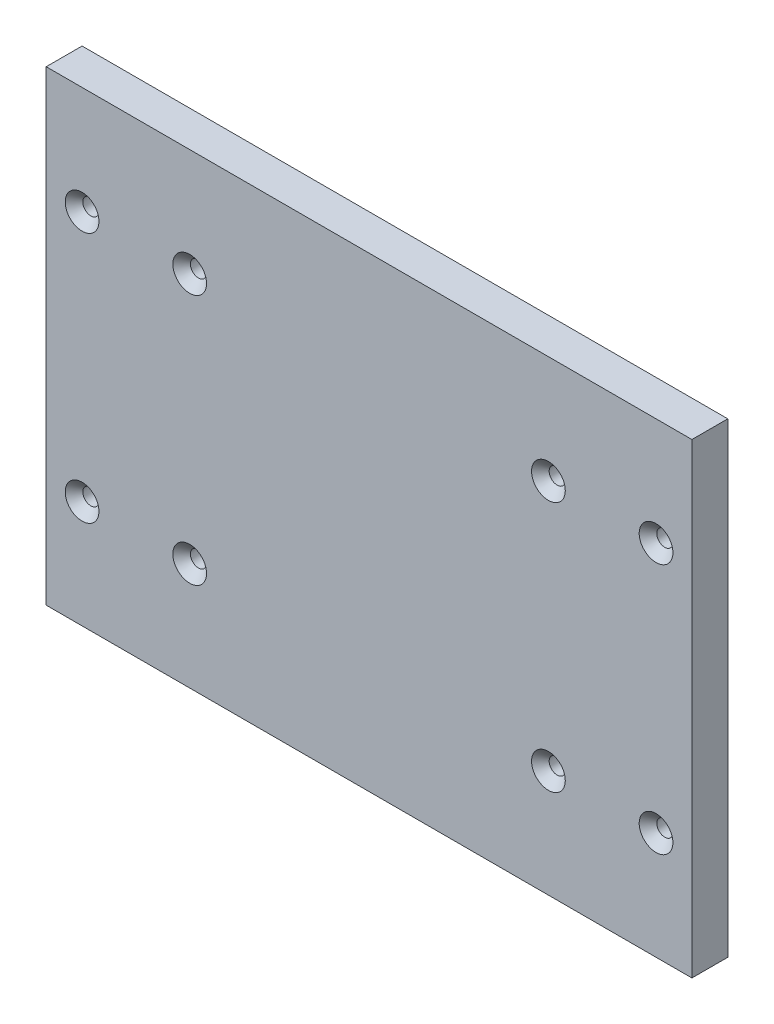
SolidWorks part; units mm, degrees
ref_plane "Front Plane" through (0, 0, 0) normal (0, 0, 1) x (1, 0, 0)
ref_plane "Top Plane" through (0, 0, 0) normal (0, 1, 0) x (1, 0, 0)
ref_plane "Right Plane" through (0, 0, 0) normal (1, 0, 0) x (0, 0, -1)
sketch "Sketch1" plane through (0, 0, 0) normal (0, 0, 1) x (1, 0, 0)
  line L1 (0, 0) -> (180, 0)
  line L2 (0, 0) -> (0, 130)
  line L3 (0, 130) -> (180, 130)
  line L4 (180, 0) -> (180, 130)
extrude "Boss-Extrude1" add sketch "Sketch1" along normal blind 10
sketch "Sketch2" plane through (0, 0, 10) normal (0, 0, 1) x (1, 0, 0)
  line L0 (0, 130) -> (0, 0) construction
  line L1 (10, 100) -> (170, 100)
  line L2 (10, 100) -> (10, 30)
  line L3 (10, 30) -> (170, 30)
  line L4 (170, 100) -> (170, 30)
  line L5 (180, 0) -> (180, 130) construction
  line L6 (180, 130) -> (0, 130) construction
  line L7 (0, 0) -> (180, 0) construction
  line L9 (10, 100) -> (40, 100)
  line L10 (10, 100) -> (10, 30)
  line L11 (10, 30) -> (40, 30)
  line L12 (40, 100) -> (40, 30)
  line L13 (170, 100) -> (140, 100)
  line L14 (170, 100) -> (170, 30)
  line L15 (170, 30) -> (140, 30)
  line L16 (140, 100) -> (140, 30)
  point P6 (0, 65)
  dimension "D1" = 10
  dimension "D2" = 10
  dimension "D3" = 30
  dimension "D4" = 30
  dimension "D5" = 30
  dimension "D6" = 30
hole_wizard "CSK for M4 Countersunk Flat Head Screw1" positions "Sketch3" profile "Sketch4" countersink size "M4" standard "ISO"
sketch "Sketch3" plane through (0, 0, 10) normal (0, 0, 1) x (1, 0, 0)
  point P0 (10, 100)
  point P3 (40, 100)
  point P6 (10, 30)
  point P9 (40, 30)
  point P12 (140, 100)
  point P15 (170, 100)
  point P18 (140, 30)
  point P21 (170, 30)
sketch "Sketch4" plane through (10, 100, 10) normal (1, 0, 0) x (0, -1, 0)
  line L0 (0, 0) -> (0, 7.3519)
  line L1 (0, 7.3519) -> (2.25, 6)
  line L2 (2.25, 6) -> (2.25, 2.45)
  line L3 (2.25, 2.45) -> (4.7, 0)
  line L5 (4.7, 0) -> (0, 0)
  line L6 (-2.25, 2.45) -> (-4.7, 0) construction
  line L10 (0, 7.3519) -> (-2.25, 6) construction
  line L11 (0, -6.35) -> (0, 107.95) construction
  dimension "Hole Dia." = 4.5
  dimension "Hole Depth" = 6
  dimension "Near C'Sink Dia." = 9.4
  dimension "Near C'Sink Angle" = 90
  dimension "Drill Angle" = 118
